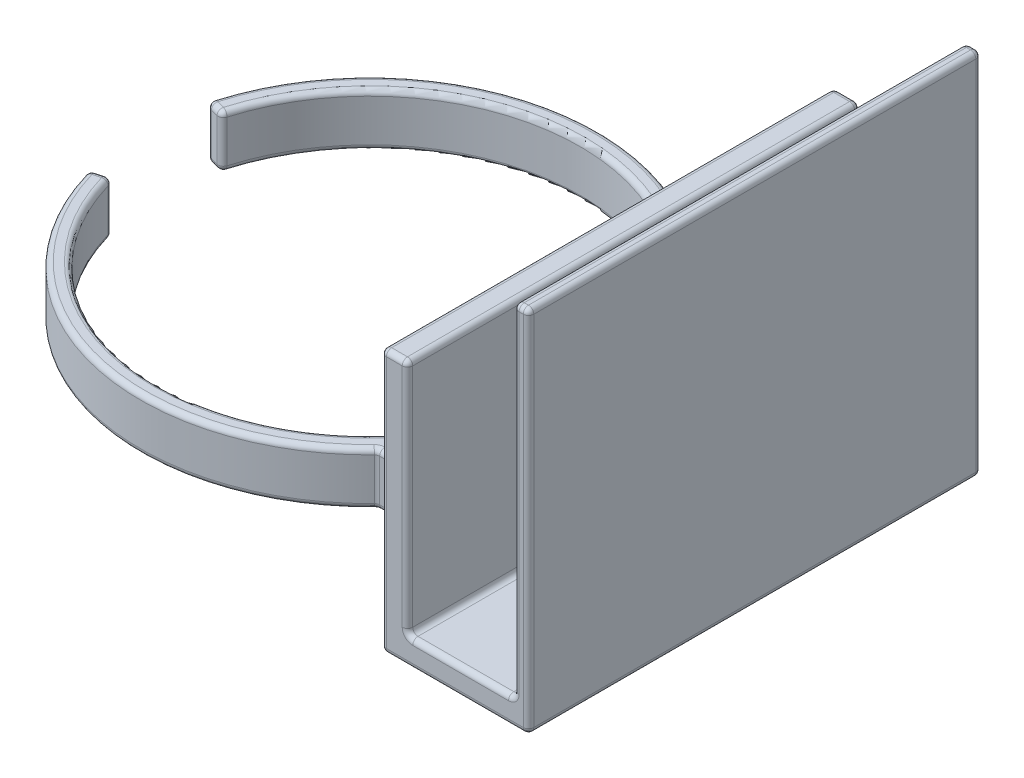
SolidWorks part; units mm, degrees
ref_plane "Front Plane" through (0, 0, 0) normal (0, 0, 1) x (1, 0, 0)
ref_plane "Top Plane" through (0, 0, 0) normal (0, 1, 0) x (1, 0, 0)
ref_plane "Right Plane" through (0, 0, 0) normal (1, 0, 0) x (0, 0, -1)
sketch "Sketch1" plane through (0, 0, 0) normal (0, 1, 0) x (1, 0, 0)
  line L1 (45.2117, 20) -> (45.2117, 5)
  line L2 (43.2117, 5) -> (45.2117, 5)
  line L3 (38.6297, 20) -> (45.2117, 20)
  line L5 (-43.5, 0) -> (73.2117, 0)
  line L6 (73.2117, 43) -> (73.2117, 0)
  line L7 (31.5, 30) -> (45.2117, 30)
  line L12 (45.2117, 30) -> (45.2117, 43)
  line L13 (45.2117, 43) -> (73.2117, 43)
  arc A1 (38.6297, 20) -> (43.2117, 5) centre (0, 0) cw
  arc A4 (31.5, 30) -> (-43.5, 0) centre (0, 0) ccw
  point P3 (73.2117, 42.8522)
  dimension "D1" = 5
  dimension "D7" = 43.5
  dimension "D5" = 43.5
  dimension "D2" = 2
  dimension "D3" = 10
  dimension "D4" = 28
  dimension "D6" = 15
  dimension "D8" = 43
extrude "Boss-Extrude1" add sketch "Sketch1" along normal blind 10
sketch "Sketch3" plane through (0, 10, 0) normal (0, 1, 0) x (1, 0, 0)
  line L2 (-42.0178, 11.2586) -> (-38.637, 10.3528)
  line L3 (-43.5, 0) -> (40, 0)
  arc A1 (-43.5, 0) -> (-42.0178, 11.2586) centre (0, 0) cw
  arc A3 (40, 0) -> (-38.637, 10.3528) centre (0, 0) ccw
  point P1 (0, 0)
  dimension "D1" = 40
  dimension "D2" = 43.5
extrude "Cut-Extrude2" cut sketch "Sketch3" against normal through all
ref_plane "Plane1" through (0, 0, 0) normal (0, 0, 1) x (1, 0, 0)
sketch "Sketch4" plane through (0, 10, 0) normal (0, 1, 0) x (1, 0, 0)
  line L0 (-5.5, 0) -> (5.5, 0) construction
  line L1 (45.2117, 43) -> (73.2117, 43)
  line L2 (45.2117, 43) -> (45.2117, 0)
  line L3 (45.2117, 0) -> (73.2117, 0)
  line L4 (73.2117, 43) -> (73.2117, 0)
  line L5 (73.2117, 0) -> (73.2117, 43) construction
extrude "Boss-Extrude2" add sketch "Sketch4" along normal blind 50
sketch "Sketch5" plane through (0, 0, 0) normal (0, -1, 0) x (1, 0, 0)
  line L0 (18.2664, 0) -> (-18.2664, 0) construction
  line L1 (73.2117, -43) -> (45.2117, -43)
  line L2 (73.2117, -43) -> (73.2117, 0)
  line L3 (73.2117, 0) -> (45.2117, 0)
  line L4 (45.2117, -43) -> (45.2117, 0)
  line L5 (45.2117, -5) -> (45.2117, -20) construction
extrude "Boss-Extrude3" add sketch "Sketch5" along normal blind 10
sketch "Sketch6" plane through (0, 60, 0) normal (0, 1, 0) x (1, 0, 0)
  line L0 (73.2117, 43) -> (45.2117, 43) construction
  line L1 (50.2117, 43) -> (70.4117, 43)
  line L2 (50.2117, 43) -> (50.2117, 0)
  line L3 (50.2117, 0) -> (70.4117, 0)
  line L4 (70.4117, 43) -> (70.4117, 0)
  line L5 (-18.2664, 0) -> (18.2664, 0) construction
  line L9 (45.2117, 43) -> (45.2117, 0) construction
  dimension "D1" = 20.2
  dimension "D3" = 5
extrude "Cut-Extrude3" cut sketch "Sketch6" against normal blind 65
mirror "Mirror1" about plane through (0, 0, 0) normal (0, 0, 1) of "Boss-Extrude1", "Cut-Extrude2", "Boss-Extrude2", "Boss-Extrude3", "Cut-Extrude3"
sketch "Sketch7" plane through (45.2117, 0, 0) normal (-1, 0, 0) x (0, 0, 1)
  line L0 (43, 60) -> (43, -10) construction
  line L1 (-43, 60) -> (43, 60)
  line L2 (-43, 60) -> (-43, 40)
  line L3 (-43, 40) -> (43, 40)
  line L4 (43, 60) -> (43, 40)
  dimension "D1" = 20
extrude "Cut-Extrude4" cut sketch "Sketch7" against normal up to next
fillet "Fillet5" radius 1 72 edges at (-10.7455, 10, 42.1519) (38.3558, 10, 30) (31.5, 5, 30) (45.2117, 5, 30) (73.2117, 25, 43) (41.6023, 10, 12.7082) (44.2117, 10, 5) (41.9207, 10, 20) (-10.7455, 0, 42.1519) (38.3558, 0, 30) (41.6023, 0, 12.7082) (38.6297, 5, 20) (41.9207, 0, 20) (45.2117, 5, 20) (45.2117, 5, 5) (44.2117, 0, 5) (31.5, 5, -30) (43.2117, 5, 5) (45.2117, 5, -30) (73.2117, 25, -43) (-42.0178, 5, 11.2586) (-38.637, 5, 10.3528) (-40.3274, 10, 10.8057) (-40.3274, 0, 10.8057) (71.8117, 60, 43) (45.2117, 10, 25) (59.2117, -10, 43) (45.2117, 0, 25) (50.2117, 17.5, 43) (70.4117, 27.5, 43) (60.3117, -5, 43) (41.6023, 0, -12.7082) (38.6297, 5, -20) (44.2117, 0, -5) (43.2117, 5, -5) (45.2117, 15, -43) (45.2117, 15, 43) (45.2117, 5, -5) (50.2117, 40, 0) (47.7117, 40, -43) (47.7117, 40, 43) (41.9207, 0, -20) (45.2117, 40, 0) (45.2117, 5, -20) (41.6023, 10, -12.7082) (44.2117, 10, -5) (41.9207, 10, -20) (38.3558, 10, -30) (-40.3274, 0, -10.8057) (-42.0178, 5, -11.2586) (40, 0, 0) (-38.637, 5, -10.3528) (40, 10, 0) (-40.3274, 10, -10.8057) (-10.7455, 10, -42.1519) (45.2117, 10, 0) (45.2117, 10, -25) (73.2117, 60, 0) (71.8117, 60, -43) (45.2117, 0, -25) (45.2117, 0, 0) (38.3558, 0, -30) (73.2117, -10, 0) (45.2117, -10, 0) (59.2117, -10, -43) (50.2117, -5, 0) (60.3117, -5, -43) (50.2117, 17.5, -43) (70.4117, -5, 0) (70.4117, 27.5, -43) (-10.7455, 0, -42.1519) (70.4117, 60, 0)
